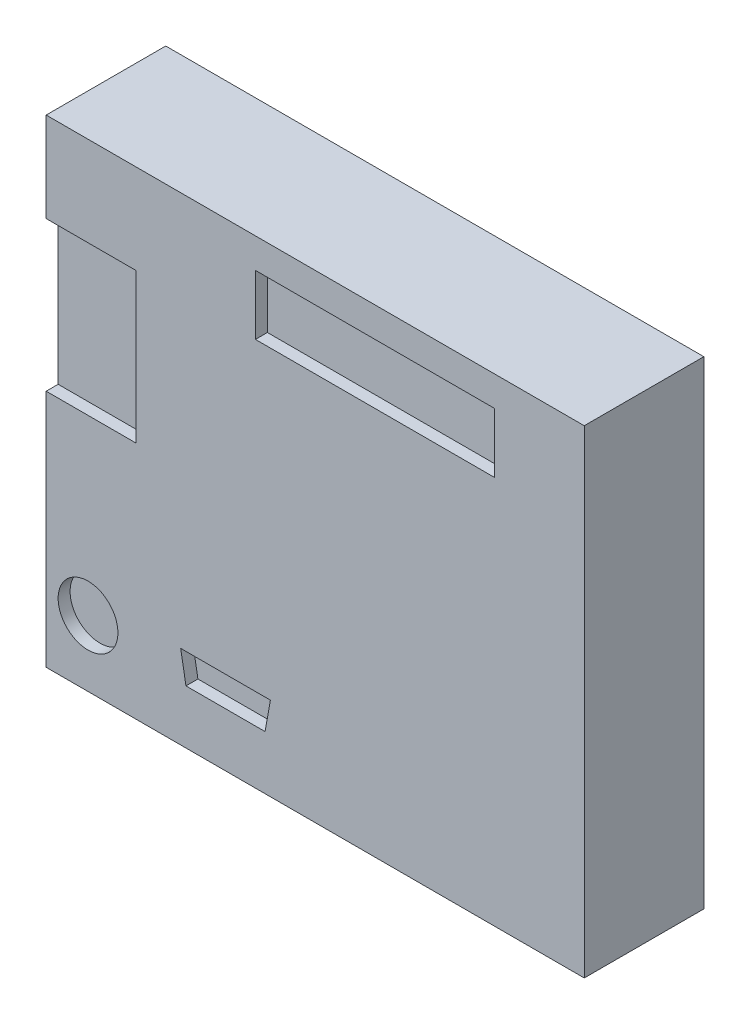
SolidWorks part; units mm, degrees
ref_plane "Plan de face" through (0, 0, 0) normal (0, 0, 1) x (1, 0, 0)
ref_plane "Plan de dessus" through (0, 0, 0) normal (0, 1, 0) x (1, 0, 0)
ref_plane "Plan de droite" through (0, 0, 0) normal (1, 0, 0) x (0, 0, -1)
sketch "Esquisse1" plane through (0, 0, 0) normal (0, 0, 1) x (1, 0, 0)
  line L1 (-45, 40) -> (45, 40)
  line L2 (-45, 40) -> (-45, -40)
  line L3 (-45, -40) -> (45, -40)
  line L4 (45, 40) -> (45, -40)
  line L5 (-45, 40) -> (45, -40) construction
  line L6 (-45, -40) -> (45, 40) construction
  point P0 (0, 0)
  dimension "D1" = 90
  dimension "D2" = 80
extrude "Boss.-Extru.1" add sketch "Esquisse1" along normal blind 20
sketch "Esquisse2" plane through (0, 0, 20) normal (0, 0, 1) x (1, 0, 0)
  line L0 (45, -40) -> (45, 40) construction
  line L1 (-10, 35) -> (30, 35)
  line L2 (-10, 35) -> (-10, 25)
  line L3 (-10, 25) -> (30, 25)
  line L4 (30, 35) -> (30, 25)
  line L5 (45, 40) -> (-45, 40) construction
  point P4 (10, 25)
  point P7 (30, 30)
  point P11 (3.5361, 13.2665)
  point P12 (5.3372, 28.9753)
  point P13 (4.8358, 27.9387)
  dimension "D1" = 10
  dimension "D2" = 40
  dimension "D3" = 35
  dimension "D4" = 10
extrude "Enlèv. mat.-Extru.1" cut sketch "Esquisse2" against normal blind 2
sketch "Esquisse3" plane through (0, 0, 20) normal (0, 0, 1) x (1, 0, 0)
  line L0 (-8.3816, -31) -> (-21.6184, -31)
  line L1 (-21.6184, -31) -> (-22.5, -26)
  line L2 (-22.5, -26) -> (-7.5, -26)
  line L3 (-7.5, -26) -> (-8.3816, -31)
  line L4 (-45, -40) -> (45, -40) construction
  line L5 (-45, 40) -> (-45, -40) construction
  point P2 (-12.986, -34.4026)
  point P7 (-15, -26)
  dimension "D1" = 80
  dimension "D2" = 15
  dimension "D3" = 5
  dimension "D4" = 80
  dimension "D5" = 9
  dimension "D6" = 30
extrude "Enlèv. mat.-Extru.2" cut sketch "Esquisse3" against normal blind 2
sketch "Esquisse4" plane through (0, 0, 20) normal (0, 0, 1) x (1, 0, 0)
  line L0 (-45, 40) -> (-45, -40) construction
  line L1 (-45, -40) -> (45, -40) construction
  circle A0 centre (-38, -29) radius 5
  dimension "D1" = 10
  dimension "D2" = 7
  dimension "D3" = 11
extrude "Enlèv. mat.-Extru.3" cut sketch "Esquisse4" against normal blind 2
sketch "Esquisse5" plane through (0, 0, 20) normal (0, 0, 1) x (1, 0, 0)
  line L0 (-45, 40) -> (-45, -40) construction
  line L1 (-45, 25) -> (-30, 25)
  line L2 (-45, 25) -> (-45, 0)
  line L3 (-45, 0) -> (-30, 0)
  line L4 (-30, 25) -> (-30, 0)
  line L5 (45, 40) -> (-45, 40) construction
  dimension "D1" = 25
  dimension "D2" = 15
  dimension "D3" = 15
extrude "Enlèv. mat.-Extru.4" cut sketch "Esquisse5" against normal blind 2
